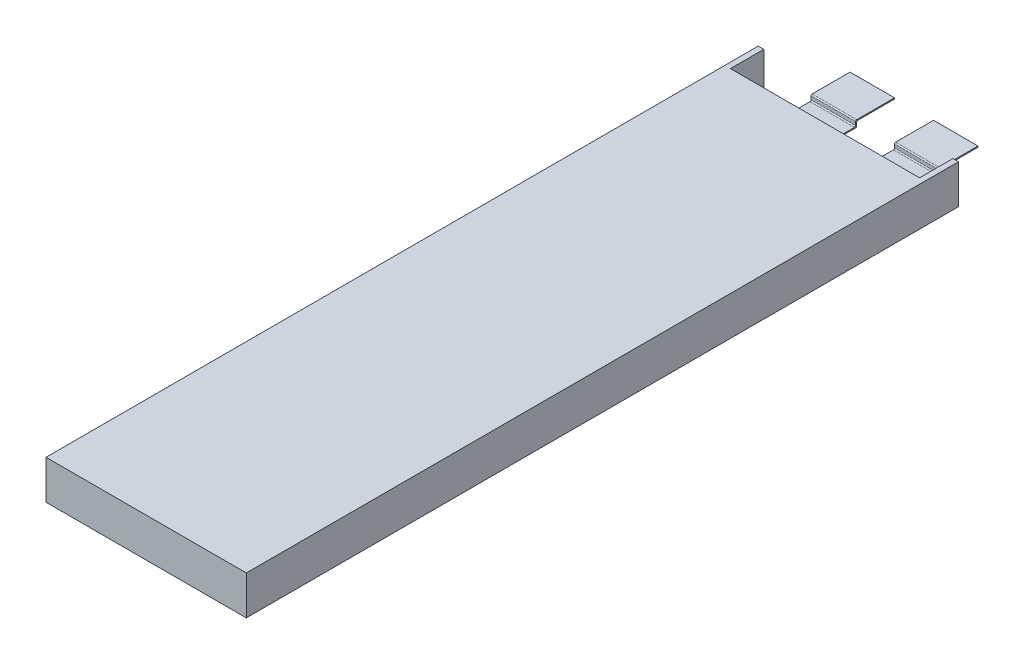
SolidWorks part; units mm, degrees
ref_plane "Front Plane" through (0, 0, 0) normal (0, 0, 1) x (1, 0, 0)
ref_plane "Top Plane" through (0, 0, 0) normal (0, 1, 0) x (1, 0, 0)
ref_plane "Right Plane" through (0, 0, 0) normal (1, 0, 0) x (0, 0, -1)
sketch "Sketch1" plane through (0, 0, 0) normal (0, 1, 0) x (1, 0, 0)
  line L1 (18, 64) -> (-18, 64)
  line L2 (18, 64) -> (18, -64)
  line L3 (18, -64) -> (-18, -64)
  line L4 (-18, 64) -> (-18, -64)
  line L5 (18, 64) -> (-18, -64) construction
  line L6 (18, -64) -> (-18, 64) construction
  point P0 (0, 0)
  dimension "D1" = 36
  dimension "D2" = 128
extrude "Boss-Extrude1" add sketch "Sketch1" along normal blind 1
sketch "Sketch2" plane through (0, 1, 0) normal (0, 1, 0) x (1, 0, 0)
  line L0 (-18, 64) -> (-18, -64) construction
  line L1 (18, 58) -> (-18, 58)
  line L2 (18, 58) -> (18, -64)
  line L3 (18, -64) -> (-18, -64)
  line L4 (-18, 58) -> (-18, -64)
  line L5 (18, 58) -> (-18, -64) construction
  line L6 (18, -64) -> (-18, 58) construction
  line L7 (18, 64) -> (-18, 64) construction
  line L8 (-18, -64) -> (18, -64) construction
  line L10 (18, -64) -> (18, 64) construction
  point P0 (0, -3)
  dimension "D1" = 6
extrude "Boss-Extrude2" add sketch "Sketch2" along normal blind 6
sketch "Sketch3" plane through (0, 1, 0) normal (0, 1, 0) x (1, 0, 0)
  line L0 (18, 58) -> (-18, 58) construction
  line L1 (-18, 64) -> (-17, 64)
  line L2 (-18, 64) -> (-18, 58)
  line L3 (-18, 58) -> (-17, 58)
  line L4 (-17, 64) -> (-17, 58)
  line L5 (0, 58) -> (0, 64) construction
  line L6 (18, 58) -> (-18, 58) construction
  line L7 (18, 64) -> (-18, 64) construction
  dimension "D1" = 1
extrude "Boss-Extrude3" add sketch "Sketch3" along normal up to surface (6 mm away) up to face at (0, 7, 3)
sketch "Sketch4" plane through (0, 0, 0) normal (1, 0, 0) x (0, 0, -1)
  line L0 (67.2, 1.2) -> (74, 1.2)
  line L1 (64, 7) -> (64, 1) construction
  line L2 (74, 1.2) -> (74, 1)
  line L3 (74, 1) -> (67.4, 1)
  line L4 (64, 0) -> (67, 0)
  line L5 (64, 0) -> (64, 0.2)
  line L6 (64, 1) -> (64, 0) construction
  line L7 (64, 0.2) -> (66.8, 0.2)
  line L8 (67, 1) -> (67, 0.4)
  line L9 (67.2, 0.8) -> (67.2, 0.2)
  arc A0 (67.2, 1.2) -> (67, 1) centre (67.2, 1) ccw
  arc A1 (66.8, 0.2) -> (67, 0.4) centre (66.8, 0.4) ccw
  arc A2 (67, 0) -> (67.2, 0.2) centre (67, 0.2) ccw
  arc A3 (67.4, 1) -> (67.2, 0.8) centre (67.4, 0.8) ccw
  dimension "D6" = 0.2
  dimension "D1" = 0.2
  dimension "D2" = 0.2
  dimension "D3" = 1
  dimension "D4" = 10
  dimension "D5" = 0.2
  dimension "D7" = 3
extrude "Boss-Extrude4" add sketch "Sketch4" along normal blind 8 from offset 3.5
mirror "Mirror1" about plane through (0, 0, 0) normal (1, 0, 0) of "Boss-Extrude4", "Boss-Extrude3"
